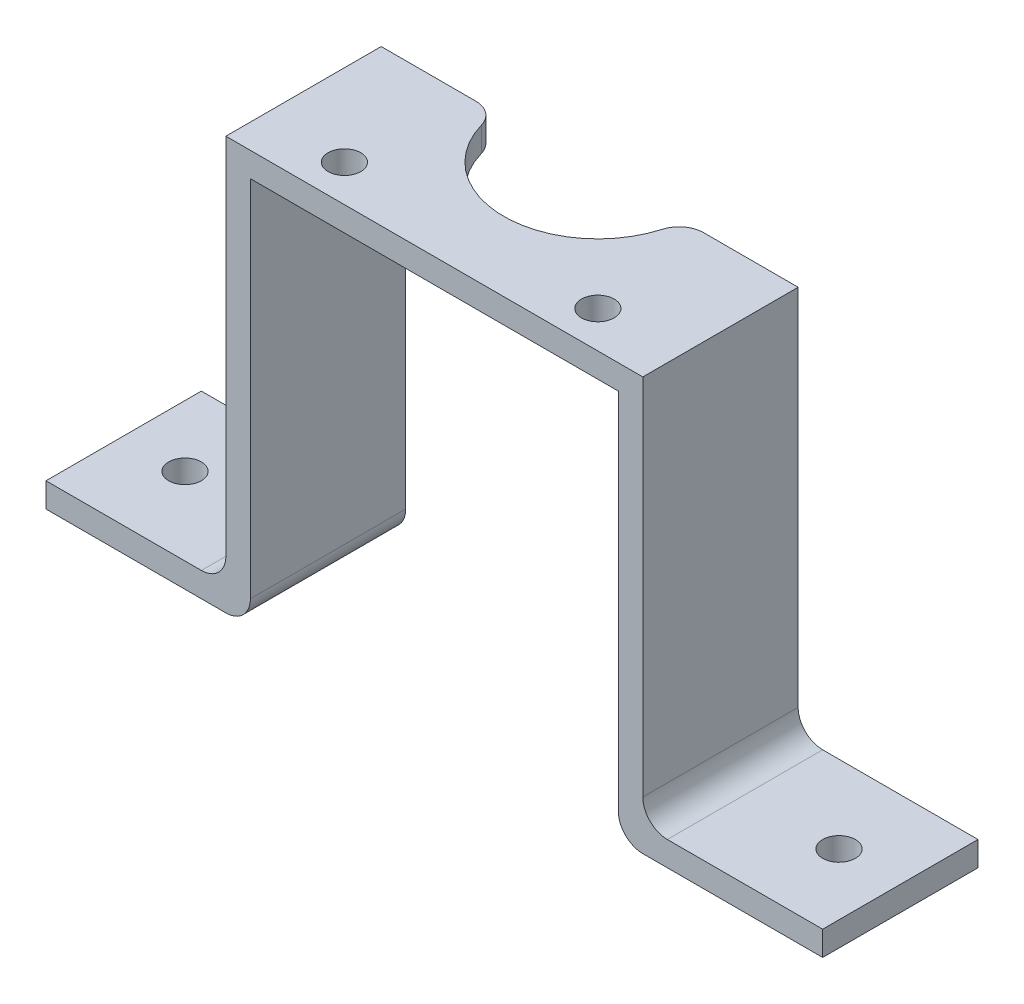
SolidWorks part; units mm, degrees
ref_plane "Front" through (0, 0, 0) normal (0, 0, 1) x (1, 0, 0)
ref_plane "Top" through (0, 0, 0) normal (0, 1, 0) x (1, 0, 0)
ref_plane "Right" through (0, 0, 0) normal (1, 0, 0) x (0, 0, -1)
sketch "Sketch1" plane through (0, 0, 0) normal (0, 0, 1) x (1, 0, 0)
  line L0 (-47.5, 0) -> (-22.5, 0)
  line L1 (-22.5, 0) -> (-22.5, 47.5)
  line L2 (-22.5, 47.5) -> (0, 47.5)
  dimension "D1" = 22.5
  dimension "D2" = 47.5
  dimension "D3" = 25
extrude "Extrude-Thin1" add sketch "Sketch1" along normal mid plane 9 thin thin type one direction reverse wall 3
mirror "Mirror1" about plane through (0, 50.5, 4.5) normal (1, 0, 0) of "Extrude-Thin1"
sketch "Sketch2" plane through (0, 50.5, 0) normal (0, 1, 0) x (1, 0, 0)
  line L0 (-15.5, 0) -> (15.5, 0) construction
  circle A0 centre (-15.5, 0) radius 2
  circle A1 centre (15.5, 0) radius 2
  point P4 (0, 0)
  dimension "D2" = 4
  dimension "D1" = 31
extrude "Cut-Extrude1" cut sketch "Sketch2" against normal through all
sketch "Sketch3" plane through (0, 0, -4.5) normal (0, 0, -1) x (-1, 0, 0)
  line L12 (-22.5, 47.5) -> (22.5, 47.5)
  line L13 (22.5, 47.5) -> (22.5, 0)
  line L14 (22.5, 0) -> (47.5, 0)
  line L15 (47.5, 0) -> (47.5, 3)
  line L16 (47.5, 3) -> (25.5, 3)
  line L17 (25.5, 3) -> (25.5, 50.5)
  line L18 (25.5, 50.5) -> (-25.5, 50.5)
  line L19 (-25.5, 50.5) -> (-25.5, 3)
  line L20 (-25.5, 3) -> (-47.5, 3)
  line L21 (-47.5, 3) -> (-47.5, 0)
  line L22 (-47.5, 0) -> (-22.5, 0)
  line L23 (-22.5, 0) -> (-22.5, 47.5)
  line L24 (-22.5, 47.5) -> (22.5, 47.5)
  line L25 (22.5, 47.5) -> (22.5, 0)
  line L26 (22.5, 0) -> (47.5, 0)
  line L27 (47.5, 0) -> (47.5, 3)
  line L28 (47.5, 3) -> (25.5, 3)
  line L29 (25.5, 3) -> (25.5, 50.5)
  line L30 (25.5, 50.5) -> (-25.5, 50.5)
  line L31 (-25.5, 50.5) -> (-25.5, 3)
  line L32 (-25.5, 3) -> (-47.5, 3)
  line L33 (-47.5, 3) -> (-47.5, 0)
  line L34 (-47.5, 0) -> (-22.5, 0)
  line L35 (-22.5, 0) -> (-22.5, 47.5)
  dimension "D1" = 0
extrude "Boss-Extrude1" add sketch "Sketch3" along normal blind 10
sketch "Sketch4" plane through (0, 50.5, 0) normal (0, 1, 0) x (1, 0, 0)
  line L0 (-25.5, -4.5) -> (25.5, -4.5) construction
  circle A0 centre (0, 15.5) radius 11.5
  dimension "D1" = 23
  dimension "D2" = 20
extrude "Cut-Extrude2" cut sketch "Sketch4" against normal through all
fillet "Fillet1" radius 3 2 edges at (-11.4564, 49, -14.5) (11.4564, 49, -14.5)
fillet "Fillet2" radius 3 4 edges at (25.5, 3, -5) (22.5, 0, -5) (-22.5, 0, -5) (-25.5, 3, -5)
sketch "Sketch5" plane through (0, 3, 0) normal (0, 1, 0) x (1, 0, 0)
  line L0 (-40, 5) -> (40, 5) construction
  line L1 (28.5, 14.5) -> (47.5, 14.5) construction
  circle A0 centre (-40, 5) radius 2
  circle A1 centre (40, 5) radius 2
  point P4 (0, 5)
  dimension "D3" = 4
  dimension "D1" = 80
  dimension "D2" = 9.5
extrude "Cut-Extrude3" cut sketch "Sketch5" against normal through all
